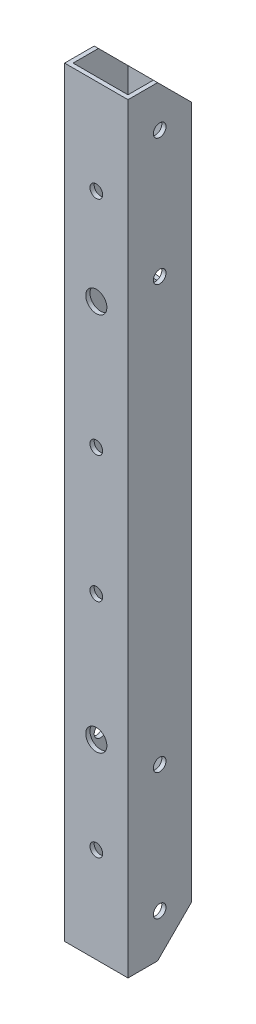
SolidWorks part; units mm, degrees
material "6061-O (SS)"
ref_plane "前视基准面" through (0, 0, 0) normal (0, 0, 1) x (1, 0, 0)
ref_plane "上视基准面" through (0, 0, 0) normal (0, 1, 0) x (1, 0, 0)
ref_plane "右视基准面" through (0, 0, 0) normal (1, 0, 0) x (0, 0, -1)
sketch "草图1" plane through (0, 0, 0) normal (0, 1, 0) x (1, 0, 0)
  line B0 (-6.5, 6.5) -> (6.5, 6.5)
  line B1 (-7.5, -7.5) -> (7.5, -7.5)
  line B2 (-7.5, -7.5) -> (-7.5, 7.5)
  line B3 (-7.5, 7.5) -> (7.5, 7.5)
  line B4 (7.5, -7.5) -> (7.5, 7.5)
  line B5 (6.5, -6.5) -> (6.5, 6.5)
  line B6 (-6.5, -6.5) -> (6.5, -6.5)
  line B7 (-6.5, -6.5) -> (-6.5, 6.5)
sketch_block_instance "块-15X15X1-1"
sketch_block "块-15X15X1" parameters "D1"=15
extrude "凸台-拉伸1" add sketch "草图1" along normal blind 180
sketch "草图2" plane through (0, 0, 7.5) normal (0, 0, 1) x (1, 0, 0)
  line L0 (-7.5, 90) -> (7.5, 90) construction
  line L1 (-7.5, 180) -> (-7.5, 0) construction
  line L2 (7.5, 180) -> (7.5, 0) construction
  line L3 (0, 180) -> (0, 0) construction
  line L4 (-7.5, 180) -> (7.5, 180) construction
  line L5 (0, 134.9013) -> (44.9013, 90) construction
  line L6 (44.9013, 90) -> (0, 45.0987) construction
  circle A0 centre (0, 134.9013) radius 2.5
  circle A1 centre (0, 45.0987) radius 2.5
  circle A2 centre (0, 187.5) radius 1.5
  circle A3 centre (0, 157.5) radius 1.5
  circle A4 centre (0, -7.5) radius 1.5
  circle A5 centre (0, 22.5) radius 1.5
  circle A6 centre (0, 105) radius 1.5
  circle A7 centre (0, 75) radius 1.5
  dimension "D1" = 5
  dimension "D2" = 63.5
  dimension "D3" = 30
  dimension "D4" = 3
  dimension "D5" = 165
  dimension "D6" = 30
  dimension "D7" = 3
extrude "切除-拉伸1" cut sketch "草图2" against normal through all
sketch "草图3" plane through (7.5, 0, 0) normal (1, 0, 0) x (0, 0, -1)
  line L0 (0, 180) -> (0, 0) construction
  line L1 (-7.5, 180) -> (7.5, 180) construction
  line L2 (-7.5, 90) -> (7.5, 90) construction
  line L3 (-7.5, 180) -> (-7.5, 0) construction
  line L4 (7.5, 180) -> (7.5, 0) construction
  line L5 (7.5, 172) -> (7.5, 180)
  line L6 (7.5, 180) -> (-0.5, 180)
  line L7 (-0.5, 180) -> (7.5, 172)
  line L8 (-0.5, 0) -> (7.5, 8)
  line L9 (7.5, 0) -> (-0.5, 0)
  line L10 (7.5, 8) -> (7.5, 0)
  circle A0 centre (0, 170) radius 1.5
  circle A1 centre (0, 140) radius 1.5
  circle A2 centre (0, 10) radius 1.5
  circle A3 centre (0, 40) radius 1.5
  dimension "D1" = 30
  dimension "D2" = 10
  dimension "D3" = 3
  dimension "D4" = 45
  dimension "D5" = 8
extrude "切除-拉伸2" cut sketch "草图3" against normal through all
